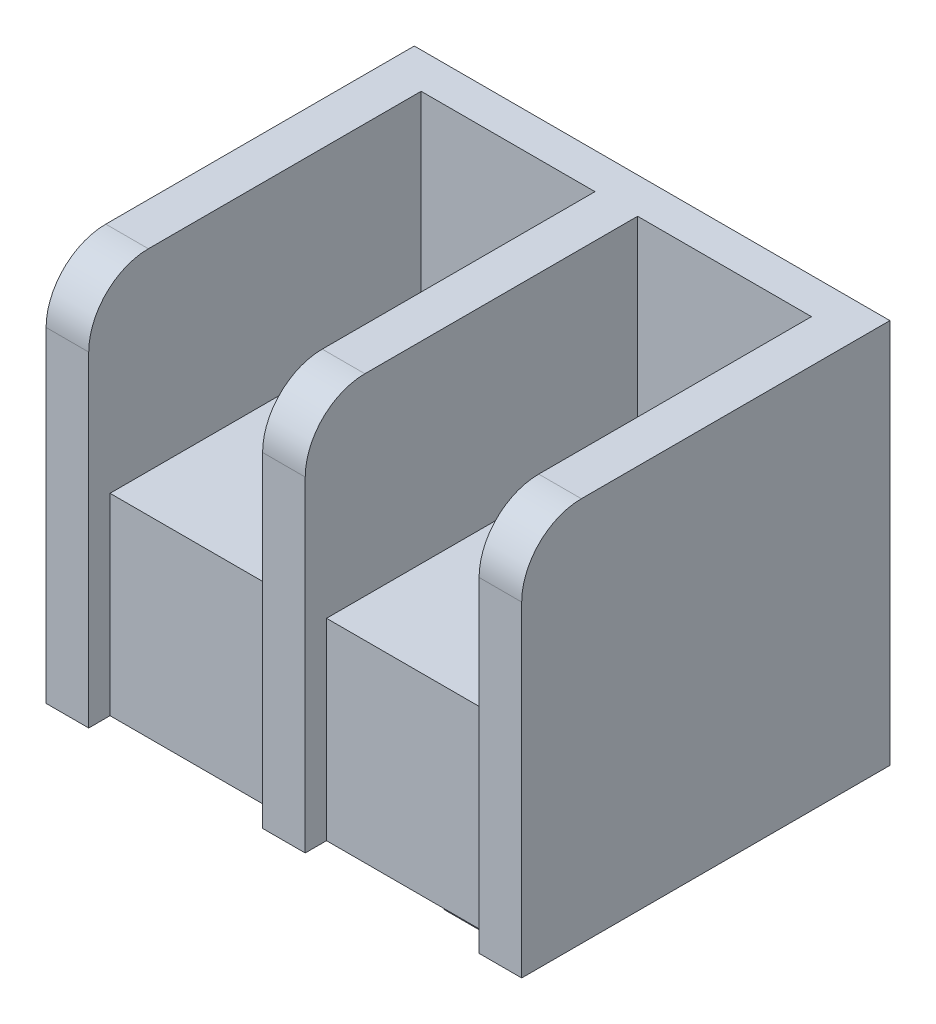
SolidWorks part; units mm, degrees
ref_plane "Front Plane" through (0, 0, 0) normal (0, 0, 1) x (1, 0, 0)
ref_plane "Top Plane" through (0, 0, 0) normal (0, 1, 0) x (1, 0, 0)
ref_plane "Right Plane" through (0, 0, 0) normal (1, 0, 0) x (0, 0, -1)
sketch "Sketch1" plane through (0, 0, 0) normal (0, 1, 0) x (1, 0, 0)
  line L1 (-13.95, 10.8) -> (13.95, 10.8)
  line L2 (-13.95, 10.8) -> (-13.95, -10.8)
  line L3 (-13.95, -10.8) -> (13.95, -10.8)
  line L4 (13.95, 10.8) -> (13.95, -10.8)
  line L5 (-13.95, 10.8) -> (13.95, -10.8) construction
  line L6 (-13.95, -10.8) -> (13.95, 10.8) construction
  point P0 (0, 0)
  dimension "D1" = 21.6
  dimension "D2" = 27.9
extrude "Boss-Extrude1" add sketch "Sketch1" along normal blind 22.6
sketch "Sketch2" plane through (0, 22.6, 0) normal (0, 1, 0) x (1, 0, 0)
  line L0 (-13.95, -10.8) -> (13.95, -10.8) construction
  line L1 (-11.45, -10.8) -> (-1.25, -10.8)
  line L2 (-11.45, -10.8) -> (-11.45, 8.7)
  line L3 (-11.45, 8.7) -> (-1.25, 8.7)
  line L4 (-1.25, -10.8) -> (-1.25, 8.7)
  line L5 (-13.95, -10.8) -> (-11.45, -10.8) construction
  line L6 (-13.95, 10.8) -> (-13.95, -10.8) construction
  dimension "D1" = 2.5
  dimension "D2" = 10.2
  dimension "D3" = 19.5
extrude "Cut-Extrude1" cut sketch "Sketch2" against normal blind 11.3
pattern_linear "LPattern1" count 2 spacing 12.7 along (1, 0, 0) of "Cut-Extrude1"
sketch "Sketch4" plane through (0, 0, 0) normal (0, -1, 0) x (-1, 0, 0)
  line L0 (-6.35, -5.2) -> (-13.95, -5.2) construction
  line L1 (-8, -4.3) -> (-4.7, -4.3)
  line L2 (-8, -4.3) -> (-8, -6.1)
  line L3 (-8, -6.1) -> (-4.7, -6.1)
  line L4 (-4.7, -4.3) -> (-4.7, -6.1)
  line L5 (-8, -4.3) -> (-4.7, -6.1) construction
  line L6 (-8, -6.1) -> (-4.7, -4.3) construction
  line L7 (-13.95, -10.8) -> (-13.95, 10.8) construction
  line L8 (-6.35, -5.2) -> (-6.35, -10.8) construction
  line L9 (13.95, -10.8) -> (-13.95, -10.8) construction
  line L10 (-6.35, -5.2) -> (-6.35, 7.8) construction
  line L11 (4.7, 8.7) -> (8, 8.7)
  line L12 (4.7, 8.7) -> (4.7, 6.9)
  line L13 (4.7, 6.9) -> (8, 6.9)
  line L14 (8, 8.7) -> (8, 6.9)
  line L15 (4.7, 8.7) -> (8, 6.9) construction
  line L16 (4.7, 6.9) -> (8, 8.7) construction
  line L17 (-6.35, 7.8) -> (6.35, 7.8) construction
  point P0 (-6.35, -5.2)
  point P9 (6.35, 7.8)
  dimension "D1" = 7.6
  dimension "D2" = 5.6
  dimension "D3" = 3.3
  dimension "D4" = 1.8
  dimension "D5" = 12.7
  dimension "D6" = 13
extrude "Boss-Extrude2" add sketch "Sketch4" along normal blind 4
chamfer "Chamfer1" distance 0.5 angle 45 8 edges at (-6.35, -4, -6.9) (-4.7, -4, -7.8) (-6.35, -4, -8.7) (-8, -4, -7.8) (6.35, -4, 6.1) (8, -4, 5.2) (6.35, -4, 4.3) (4.7, -4, 5.2)
sketch "Sketch6" plane through (0, 0, 10.8) normal (0, 0, 1) x (1, 0, 0)
  line L0 (-13.95, 0) -> (13.95, 0) construction
  line L1 (-11.45, 11.3) -> (-1.25, 11.3)
  line L2 (-11.45, 11.3) -> (-11.45, 0)
  line L3 (-11.45, 0) -> (-1.25, 0)
  line L4 (-1.25, 11.3) -> (-1.25, 0)
  line L5 (-1.25, 11.3) -> (-1.25, 22.6) construction
extrude "Cut-Extrude3" cut sketch "Sketch6" against normal blind 1.25
pattern_linear "LPattern2" count 2 spacing 12.7 along (1, 0, 0) of "Cut-Extrude3"
sketch "Sketch7" plane through (0, 11.3, 0) normal (0, 1, 0) x (1, 0, 0)
  line L0 (-6.35, -9.55) -> (-6.35, 1.3) construction
  line L1 (-1.25, -9.55) -> (-11.45, -9.55) construction
  circle A0 centre (-6.35, 1.3) radius 3.75
  dimension "D2" = 7.5
  dimension "D1" = 10.85
extrude "Boss-Extrude3" add sketch "Sketch7" along normal blind 2.5
fillet "Fillet1" radius 1 1 edges at (-6.35, 13.8, 2.45)
pattern_linear "LPattern3" count 2 spacing 12.7 along (1, 0, 0) of "Boss-Extrude3", "Fillet1"
fillet "Fillet2" radius 3.5 3 edges at (-12.7, 22.6, 10.8) (0, 22.6, 10.8) (12.7, 22.6, 10.8)
